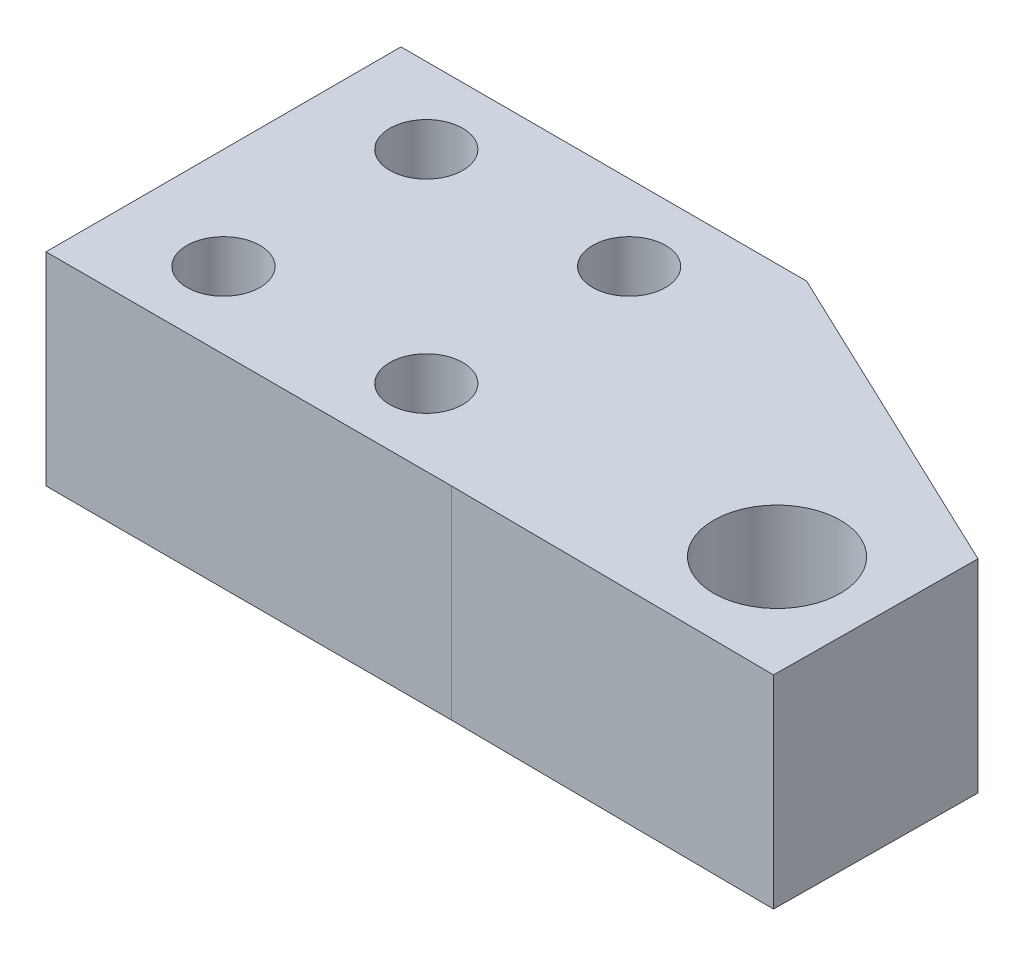
SolidWorks part; units mm, degrees
ref_plane "Front Plane" through (0, 0, 0) normal (0, 0, 1) x (1, 0, 0)
ref_plane "Top Plane" through (0, 0, 0) normal (0, 1, 0) x (1, 0, 0)
ref_plane "Right Plane" through (0, 0, 0) normal (1, 0, 0) x (0, 0, -1)
sketch "Sketch1" plane through (0, 0, 0) normal (0, 1, 0) x (1, 0, 0)
  line L0 (25.4, 22.225) -> (45.8235, 12.5328)
  line L2 (0, 0) -> (0, 22.225)
  line L3 (0, 22.225) -> (25.4, 22.225)
  line L8 (45.8235, 12.5328) -> (45.7193, -0.1667)
  line L9 (0, 0) -> (25.4, 0)
  line L10 (25.4, 0) -> (45.7193, -0.1667)
  circle A0 centre (39.4226, 6.35) radius 3.9687
  circle A1 centre (6.35, 4.7625) radius 2.286
  circle A2 centre (19.05, 4.7625) radius 2.286
  circle A3 centre (19.05, 17.4625) radius 2.286
  circle A4 centre (6.35, 17.4625) radius 2.286
  point P3 (0, 11.1125)
  point P7 (45.72, 0)
  point P19 (45.6733, -2.0652)
  point P20 (45.6551, -2.4354)
  point P21 (45.6243, -1.97)
  point P22 (45.72, 0)
  point P23 (45.5145, -2.8826)
  dimension "D1" = 7.9375
  dimension "D12" = 4.572
  dimension "D2" = 6.4649
  dimension "D3" = 22.225
  dimension "D4" = 6.35
  dimension "D5" = 6.35
  dimension "D6" = 25.4
  dimension "D7" = 20.32
  dimension "D8" = 6.35
  dimension "D9" = 6.35
  dimension "D13" = 12.7
  dimension "D10" = 2
  dimension "D11" = 2
extrude "Boss-Extrude1" add sketch "Sketch1" along normal mid plane 12.7
